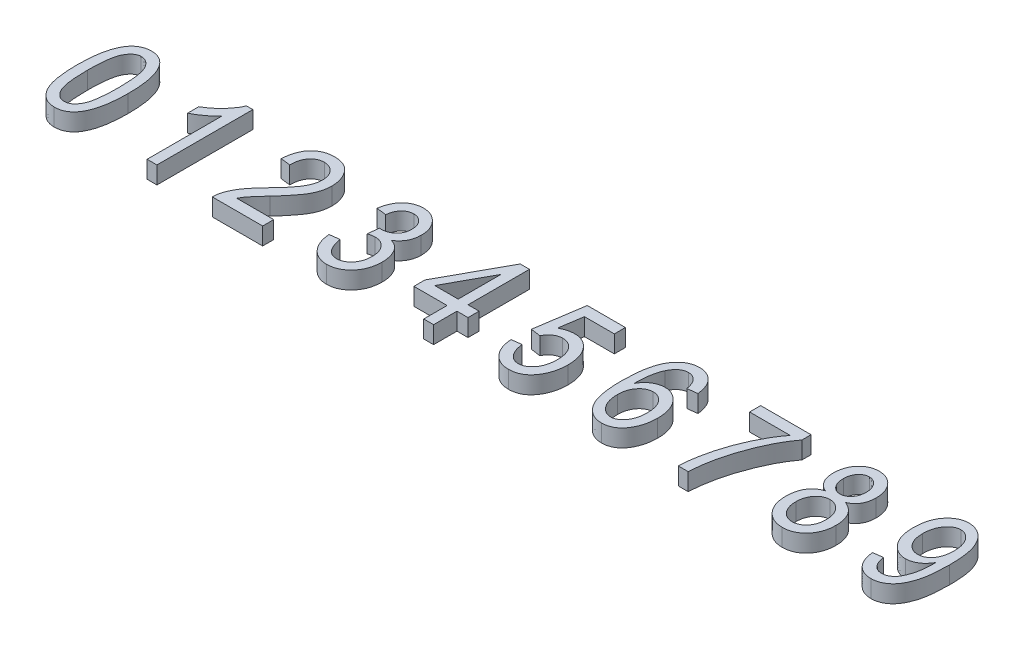
SolidWorks part; units mm, degrees
ref_plane "前视基准面" through (0, 0, 0) normal (0, 0, 1) x (1, 0, 0)
ref_plane "上视基准面" through (0, 0, 0) normal (0, 1, 0) x (1, 0, 0)
ref_plane "右视基准面" through (0, 0, 0) normal (1, 0, 0) x (0, 0, -1)
sketch "草图1" plane through (0, 0, 0) normal (0, 1, 0) x (1, 0, 0)
  line L0 (269.6667, 416) -> (1348.3333, 416) construction
  line L1 (226, 409) -> (1130, 409) construction
  line L2 (226, 409) -> (1130, 409) construction
  text T0 "0 1 2 3 4 5 6 7 8 9 " font "Arial Narrow" height in points 72
  dimension "D1" = 226
  dimension "D5" = 409
  dimension "D6" = 416
extrude "凸台-拉伸1" add sketch "草图1" along normal blind 4
